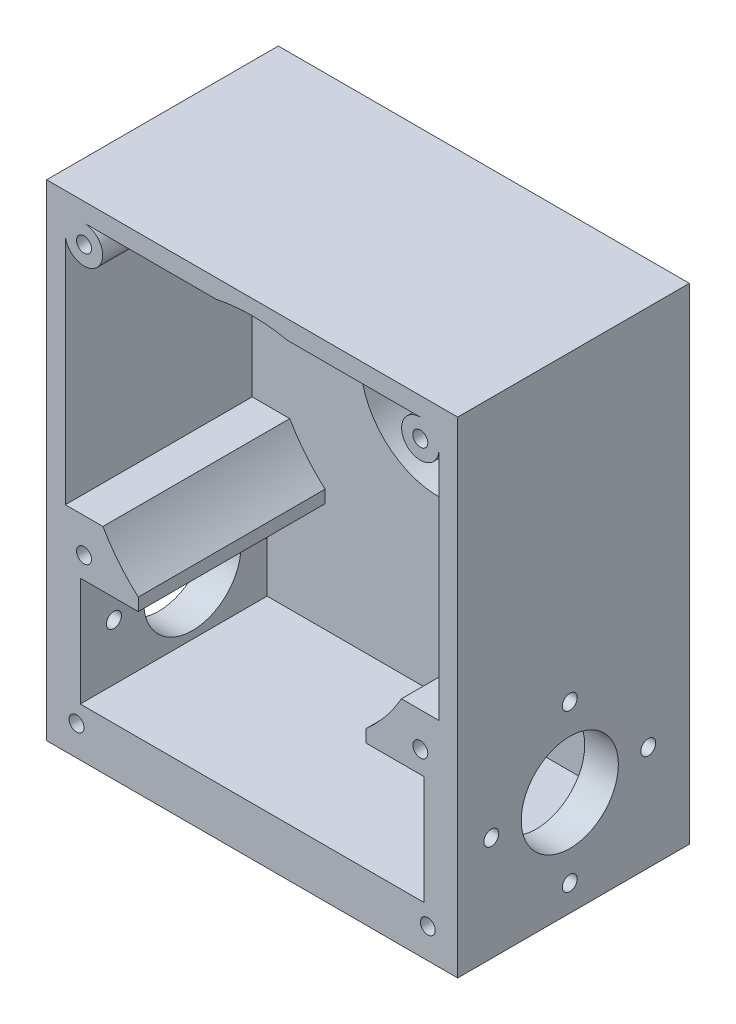
SolidWorks part; units mm, degrees
ref_plane "Front Plane" through (0, 0, 0) normal (0, 0, 1) x (1, 0, 0)
ref_plane "Top Plane" through (0, 0, 0) normal (0, 1, 0) x (1, 0, 0)
ref_plane "Right Plane" through (0, 0, 0) normal (1, 0, 0) x (0, 0, -1)
sketch "Sketch1" plane through (0, 0, 0) normal (0, 0, 1) x (1, 0, 0)
  line L1 (-55, -60) -> (55, -60)
  line L2 (-55, -60) -> (-55, 70)
  line L3 (-55, 70) -> (55, 70)
  line L4 (55, -60) -> (55, 70)
  dimension "D1" = 110
  dimension "D2" = 130
  dimension "D3" = 55
  dimension "D4" = 60
extrude "Boss-Extrude1" add sketch "Sketch1" along normal mid plane 10
sketch "Sketch6" plane through (0, 0, -5) normal (0, 0, -1) x (-1, 0, 0)
  circle A0 centre (0, 20) radius 21
  dimension "D1" = 42
  dimension "D2" = 20
sketch "Sketch9" plane through (0, 0, 0) normal (1, 0, 0) x (0, 0, -1)
  line L0 (20.8617, 20) -> (-52.2227, 20) construction
  line L1 (-52.2227, 20) -> (-52.2227, -32) construction
  dimension "D1" = 52
sketch "Sketch10" plane through (0, -60, 0) normal (0, -1, 0) x (1, 0, 0)
  line L1 (-55, -5) -> (55, -5)
  line L2 (-55, -5) -> (-55, 55)
  line L3 (-55, 55) -> (55, 55)
  line L4 (55, -5) -> (55, 55)
  dimension "D1" = 110
  dimension "D2" = 60
extrude "Boss-Extrude4" add sketch "Sketch10" against normal blind 13
extrude "Cut-Extrude2" cut sketch "Sketch6" against normal blind 30
sketch "Sketch16" plane through (0, 0, -5) normal (0, 0, -1) x (-1, 0, 0)
  circle A0 centre (0, 20) radius 27.5
  circle A3 centre (0, 20) radius 21
  circle A4 centre (0, 20) radius 21
  dimension "D1" = 55
  dimension "D2" = 0
sketch "Sketch18" plane through (0, 0, 5) normal (0, 0, 1) x (1, 0, 0)
  line L0 (-55, -47) -> (-39, -47)
  line L1 (55, -47) -> (-55, -47) construction
  line L2 (-39, -47) -> (-39, -17.8222)
  line L3 (-39, -17.8222) -> (-30.4822, -17.8222)
  line L4 (0, -77.0477) -> (0, 71.7935) construction
  line L5 (55, -47) -> (39, -47)
  line L6 (39, -17.8222) -> (30.4822, -17.8222)
  line L7 (39, -47) -> (39, -17.8222)
  line L8 (-55, -47) -> (-55, 70)
  line L9 (-55, 70) -> (55, 70)
  line L10 (55, 70) -> (55, -47)
  line L11 (-30.4822, -17.8222) -> (-30.4822, -14.4505)
  line L12 (30.4822, -17.8222) -> (30.4822, -14.4505)
  arc A0 (30.4822, -14.4505) -> (-30.4822, -14.4505) centre (0, 20) ccw
  dimension "D1" = 92
  dimension "D2" = 16
  dimension "D3" = 16
extrude "Boss-Extrude8" add sketch "Sketch18" along normal blind 50
sketch "Sketch23" plane through (-39, 0, 0) normal (1, 0, 0) x (0, 0, -1)
  line L0 (-5, -47) -> (-5, -17.8222) construction
  line L2 (20.8617, 20) -> (-52.2227, 20) construction
  circle A0 centre (-25, -32) radius 13
  dimension "D2" = 26
  dimension "D1" = 20
  dimension "D3" = 52
extrude "Cut-Extrude5" cut sketch "Sketch23" against normal through all
sketch "Sketch26" plane through (0, 0, 55) normal (0, 0, 1) x (1, 0, 0)
  line L0 (-55, 70) -> (-55, -60) construction
  line L2 (55, 70) -> (-55, 70) construction
  line L3 (0, 70) -> (0, 46.3752) construction
  line L4 (55, -60) -> (-55, -60) construction
  line L5 (0, -60) -> (0, -47) construction
  line L6 (39, -47) -> (-39, -47) construction
  circle A0 centre (-45, 60) radius 2
  circle A1 centre (45, 60) radius 2
  circle A2 centre (-47, -52) radius 2
  circle A3 centre (47, -52) radius 2
  circle A4 centre (-45, -12) radius 2
  circle A5 centre (45, -12) radius 2
  dimension "D1" = 4
  dimension "D2" = 10
  dimension "D3" = 10
  dimension "D4" = 4
  dimension "D5" = 8
  dimension "D6" = 8
  dimension "D7" = 4
  dimension "D8" = 4
  dimension "D9" = 48
  dimension "D10" = 48
extrude "Cut-Extrude8" cut sketch "Sketch26" against normal blind 10
sketch "Sketch15" plane through (-55, 0, 0) normal (-1, 0, 0) x (0, 0, 1)
  line L0 (-20.8617, 20) -> (52.2227, 20) construction
  line L1 (-5, 70) -> (-5, -60) construction
  circle A0 centre (20, -32) radius 9.9855
  dimension "D1" = 52
  dimension "D2" = 25
sketch "Sketch31" plane through (0, 0, 55) normal (0, 0, 1) x (1, 0, 0)
  line L5 (-50, 65) -> (-50, -2.8222) construction
  line L6 (-50, -55) -> (50, -55) construction
  line L7 (50, -55) -> (50, -12) construction
  line L8 (50, 65) -> (-50, 65) construction
  line L18 (-50, -17.8222) -> (-50, -12)
  line L19 (-50, 65) -> (50, 65)
  line L20 (50, 65) -> (50, -2.8222)
  line L21 (-50, -17.8222) -> (-50, -12) construction
  line L22 (-50, -2.8222) -> (50, -2.8222)
  line L23 (50, -2.8222) -> (50, 65) construction
  line L24 (50, -12) -> (50, -17.8222)
  line L25 (-50, -12) -> (-50, -55) construction
  line L26 (-50, -2.8222) -> (-50, 65)
  circle A1 centre (-45, 60) radius 5
  circle A2 centre (45, 60) radius 5
  circle A4 centre (-45, -12) radius 5
  circle A5 centre (45, -12) radius 5
  arc M27 (-30.4822, -14.4505) -> (30.4822, -14.4505) centre (0, 20) cw
  dimension "D1" = 15
  dimension "D2" = 10
  dimension "D3" = 10
  dimension "D4" = 10
  dimension "D8" = 10
  dimension "D5" = 120
  dimension "D6" = 100
  dimension "D7" = 120
extrude "Cut-Extrude23" cut sketch "Sketch31" against normal blind 50 contours A1 L26 L22 L19 M27 | L22 L19 M27 | A2 L19 L22 L20 M27
sketch "Sketch37" plane through (0, 0, -5) normal (0, 0, -1) x (-1, 0, 0)
  line L0 (0, 20) -> (0, 48.6697) construction
  line L1 (0, 20) -> (-30.4458, 20) construction
  line L2 (0, 20) -> (-25.1221, 45.1221) construction
  line L3 (0, 20) -> (27.6241, 20) construction
  circle A0 centre (-17, 37) radius 1.5
  circle A1 centre (17, 37) radius 1.5
  circle A2 centre (-17, 3) radius 1.5
  circle A3 centre (17, 3) radius 1.5
  dimension "D2" = 3
  dimension "D3" = 17
  dimension "D1" = 45
extrude "Cut-Extrude25" cut sketch "Sketch37" against normal blind 4
sketch "Sketch39" plane through (0, 0, -5) normal (0, 0, -1) x (-1, 0, 0)
  line L1 (-55, 70) -> (55, 70)
  line L2 (-55, 70) -> (-55, -60)
  line L3 (-55, -60) -> (55, -60)
  line L4 (55, 70) -> (55, -60)
  circle A0 centre (0, 20) radius 21
  circle A1 centre (-17, 37) radius 1.5
  circle A2 centre (17, 37) radius 1.5
  circle A3 centre (17, 3) radius 1.5
  circle A4 centre (-17, 3) radius 1.5
  dimension "D1" = 3
extrude "Boss-Extrude10" add sketch "Sketch39" along normal blind 2
ref_plane "Plane1" through (0, 0, 55) normal (0, 0, 1) x (1, 0, 0)
sketch "Sketch41" plane through (-39, 0, 0) normal (1, 0, 0) x (0, 0, -1)
  line L1 (-55, -47) -> (-5, -47)
  line L2 (-55, -47) -> (-55, -17.8222)
  line L3 (-55, -17.8222) -> (-5, -17.8222)
  line L4 (-5, -47) -> (-5, -17.8222)
extrude "Cut-Extrude26" cut sketch "Sketch41" against normal blind 7
mirror "Mirror1" about plane through (0, 0, 0) normal (1, 0, 0) of "Cut-Extrude26"
mirror "Mirror2" about plane through (0, 0, 0) normal (1, 0, 0) of "Cut-Extrude5"
sketch "Sketch43" plane through (55, 0, 0) normal (1, 0, 0) x (0, 0, -1)
  circle A1 centre (-25, -11) radius 2
  circle A2 centre (-4, -32) radius 2
  circle A3 centre (-25, -53) radius 2
  circle A4 centre (-46, -32) radius 2
  point P14 (-25, -32)
  dimension "D2" = 4
  dimension "D3" = 4
extrude "Cut-Extrude27" cut sketch "Sketch43" against normal blind 9
mirror "Mirror3" about plane through (0, 0, 0) normal (1, 0, 0) of "Cut-Extrude27"
